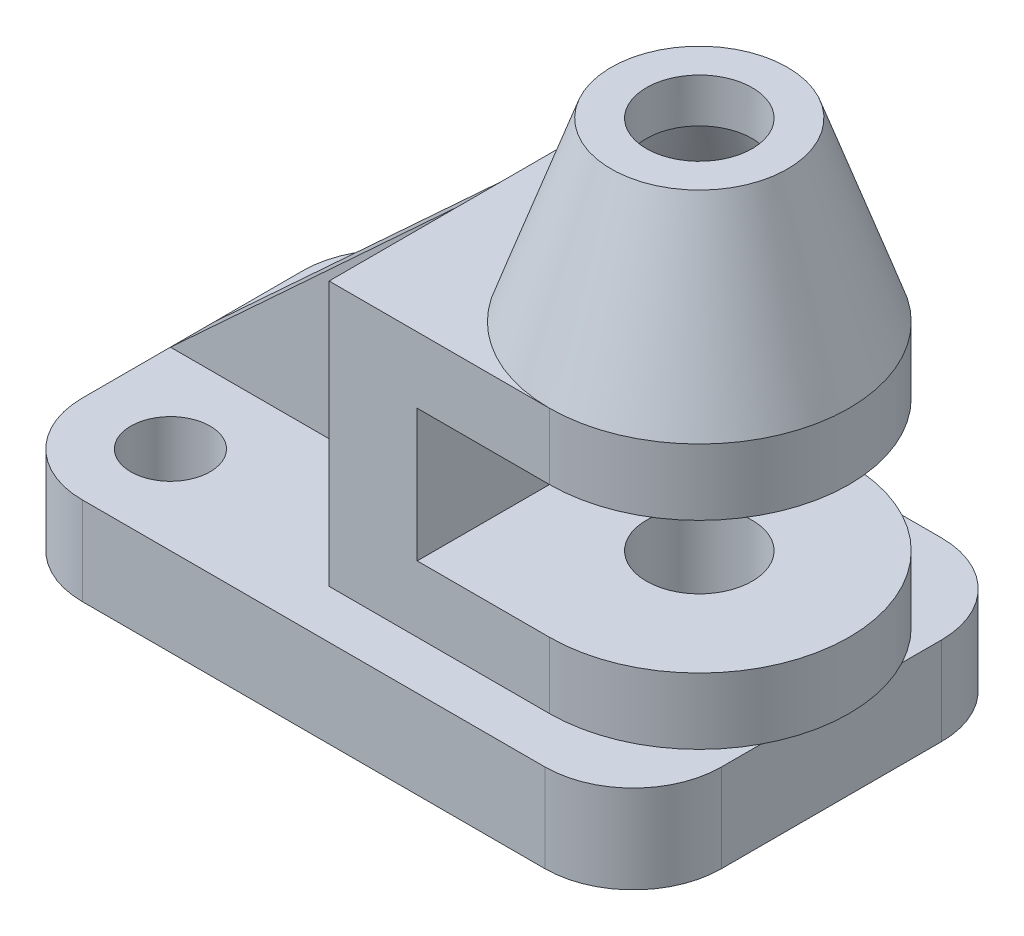
SolidWorks part; units mm, degrees
ref_plane "Front Plane" through (0, 0, 0) normal (0, 0, 1) x (1, 0, 0)
ref_plane "Top Plane" through (0, 0, 0) normal (0, 1, 0) x (1, 0, 0)
ref_plane "Right Plane" through (0, 0, 0) normal (1, 0, 0) x (0, 0, -1)
sketch "Sketch1" plane through (0, 0, 0) normal (0, 1, 0) x (1, 0, 0)
  line L1 (-72.5, 45) -> (72.5, 45)
  line L2 (-72.5, 45) -> (-72.5, -45)
  line L3 (-72.5, -45) -> (72.5, -45)
  line L4 (72.5, 45) -> (72.5, -45)
  line L5 (-72.5, 45) -> (72.5, -45) construction
  line L6 (-72.5, -45) -> (72.5, 45) construction
  circle A0 centre (-52.5, 25) radius 9
  circle A1 centre (-52.5, -25) radius 9
  point P0 (0, 0)
  dimension "D3" = 50
  dimension "D6" = 18
  dimension "D7" = 18
  dimension "D1" = 145
  dimension "D2" = 90
  dimension "D4" = 20
  dimension "D5" = 20
  dimension "D8" = 20
  dimension "D9" = 20
extrude "Boss-Extrude1" add sketch "Sketch1" along normal blind 20
fillet "Fillet2" radius 20 4 edges at (72.5, 10, 45) (72.5, 10, -45) (-72.5, 10, 45) (-72.5, 10, -45)
sketch "Sketch2" plane through (0, 20, 0) normal (0, 1, 0) x (1, 0, 0)
  line L0 (-7.5, 34) -> (-7.5, -34)
  line L3 (-7.5, -34) -> (42.5, -34)
  line L4 (42.5, 34) -> (-7.5, 34)
  line L5 (-72.5, 25) -> (-72.5, -25) construction
  arc A0 (42.5, -34) -> (42.5, 34) centre (42.5, 0) ccw
  dimension "D1" = 68
  dimension "D2" = 50
  dimension "D3" = 50
  dimension "D4" = 65
extrude "Boss-Extrude3" add sketch "Sketch2" along normal blind 60 from offset 0
sketch "Sketch3" plane through (0, 80, 0) normal (0, 1, 0) x (1, 0, 0)
  line L1 (12.5, 34) -> (12.5, -34)
  line L3 (42.5, 34) -> (-7.5, 34)
  line L4 (-7.5, 34) -> (-7.5, -34)
  line L5 (-7.5, -34) -> (42.5, -34)
  line L6 (42.5, 34) -> (-7.5, 34)
  line L7 (-7.5, 34) -> (-7.5, -34)
  line L8 (-7.5, -34) -> (42.5, -34)
  arc A1 (42.5, -34) -> (42.5, 34) centre (42.5, 0) ccw
  arc A2 (42.5, -34) -> (42.5, 34) centre (42.5, 0) ccw
  line M5 (42.5, 34) -> (-7.5, 34)
  line M7 (-7.5, -34) -> (42.5, -34)
  arc M8 (42.5, -34) -> (42.5, 34) centre (42.5, 0) ccw
  dimension "D2" = 20
  dimension "D1" = 0
sketch "Sketch5" plane through (0, 80, 0) normal (0, 1, 0) x (1, 0, 0)
extrude "Cut-Extrude1" cut sketch "Sketch3" against normal blind 30 from offset 15 contours L1 M5 M7 M8 offset against normal yes
sketch "Sketch8" plane through (0, 0, 0) normal (0, 0, 1) x (1, 0, 0)
  line L0 (-7.5, 80) -> (-72.5, 20)
rib "Rib4" sketch "Sketch8" sketch "Sketch8" thickness 10 extrusion direction parallel to sketch draft on no parameters "D1"=10
sketch "Sketch13" plane through (0, 0, 0) normal (1, 0, 0) x (0, 0, -1)
  line L0 (-34, 80) -> (34, 80)
sketch "Sketch14" plane through (0, 80, 0) normal (0, 1, 0) x (1, 0, 0)
  line L0 (42.5, -34) -> (42.5, 34) construction
  line L1 (0, -34) -> (0, 34) construction
  arc A0 (42.5, -34) -> (42.5, 34) centre (42.5, 0) ccw construction
  dimension "D1" = 42.5
sketch "Sketch16" plane through (0, 80, 0) normal (0, 1, 0) x (1, 0, 0)
ref_plane "Plane2" through (42.5, 0, 0) normal (1, 0, 0) x (0, 0, -1)
sketch "Sketch17" plane through (42.5, 0, 0) normal (1, 0, 0) x (0, 0, -1)
  line L0 (0, 80) -> (0, 120)
  line L1 (-34, 80) -> (34, 80) construction
  line L2 (0, 120) -> (20, 120)
  line L3 (20, 120) -> (34, 80)
  dimension "D1" = 20
  dimension "D2" = 40
  dimension "D3" = 34
revolve "Revolve-Thin1" add sketch "Sketch17" angle 360 about L0
sketch "Sketch18" plane through (0, 120, 0) normal (0, 1, 0) x (1, 0, 0)
  circle A0 centre (42.5, 0) radius 12
  dimension "D1" = 24
extrude "Cut-Extrude2" cut sketch "Sketch18" against normal through all
